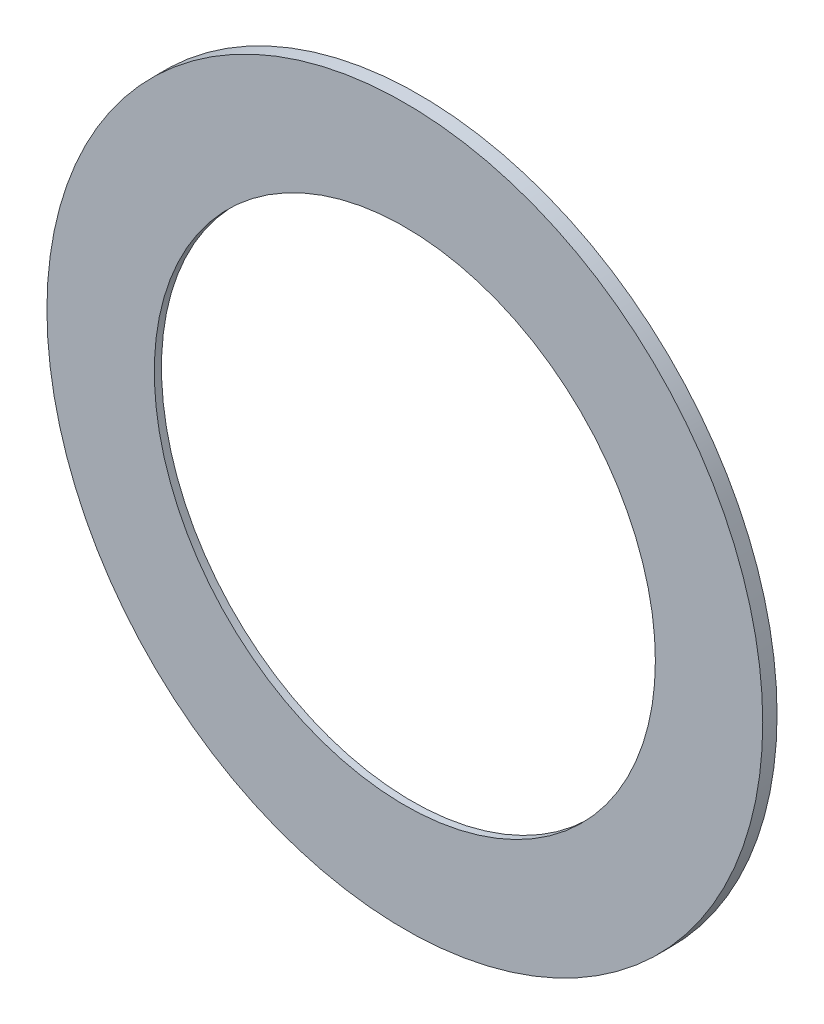
SolidWorks part; units mm, degrees
ref_plane "Alzado" through (0, 0, 0) normal (0, 0, 1) x (1, 0, 0)
ref_plane "Planta" through (0, 0, 0) normal (0, 1, 0) x (1, 0, 0)
ref_plane "Vista lateral" through (0, 0, 0) normal (1, 0, 0) x (0, 0, -1)
sketch "Croquis1" plane through (0, 0, 0) normal (0, 0, 1) x (1, 0, 0)
  circle A0 centre (0, 0) radius 200
  circle A1 centre (0, 0) radius 160
  circle A3 centre (145.6231, 105.8013) radius 5.4
  circle A4 centre (164.4382, 73.2126) radius 5.4
  circle A5 centre (176.0666, 37.4241) radius 5.4
  circle A6 centre (180, 0) radius 5.4
  circle A7 centre (176.0666, -37.4241) radius 5.4
  circle A8 centre (164.4382, -73.2126) radius 5.4
  circle A9 centre (145.6231, -105.8013) radius 5.4
  circle A10 centre (120.4435, -133.7661) radius 5.4
  circle A11 centre (90, -155.8846) radius 5.4
  circle A12 centre (55.6231, -171.1902) radius 5.4
  circle A13 centre (18.8151, -179.0139) radius 5.4
  circle A14 centre (-18.8151, -179.0139) radius 5.4
  circle A15 centre (-55.6231, -171.1902) radius 5.4
  circle A16 centre (-90, -155.8846) radius 5.4
  circle A17 centre (-120.4435, -133.7661) radius 5.4
  circle A18 centre (-145.6231, -105.8013) radius 5.4
  circle A19 centre (-164.4382, -73.2126) radius 5.4
  circle A20 centre (-176.0666, -37.4241) radius 5.4
  circle A21 centre (-180, 0) radius 5.4
  circle A22 centre (-176.0666, 37.4241) radius 5.4
  circle A23 centre (-164.4382, 73.2126) radius 5.4
  circle A24 centre (-145.6231, 105.8013) radius 5.4
  circle A25 centre (-120.4435, 133.7661) radius 5.4
  circle A26 centre (-90, 155.8846) radius 5.4
  circle A27 centre (-55.6231, 171.1902) radius 5.4
  circle A28 centre (-18.8151, 179.0139) radius 5.4
  circle A29 centre (18.8151, 179.0139) radius 5.4
  circle A30 centre (55.6231, 171.1902) radius 5.4
  circle A31 centre (90, 155.8846) radius 5.4
  circle A32 centre (120.4435, 133.7661) radius 5.4
  point P87 (-72.8115, -163.5374)
  point P94 (37.2191, -175.1021)
  point P111 (170.2524, 55.3184)
  point P124 (0, 179.0139)
extrude "Saliente-Extruir1" add sketch "Croquis1" along normal blind 4
sketch "Croquis2" plane through (0, 0, 4) normal (0, 0, 1) x (1, 0, 0)
  circle A0 centre (0, 0) radius 200
  circle A1 centre (0, 0) radius 140
extrude "Saliente-Extruir2" add sketch "Croquis2" along normal blind 4
